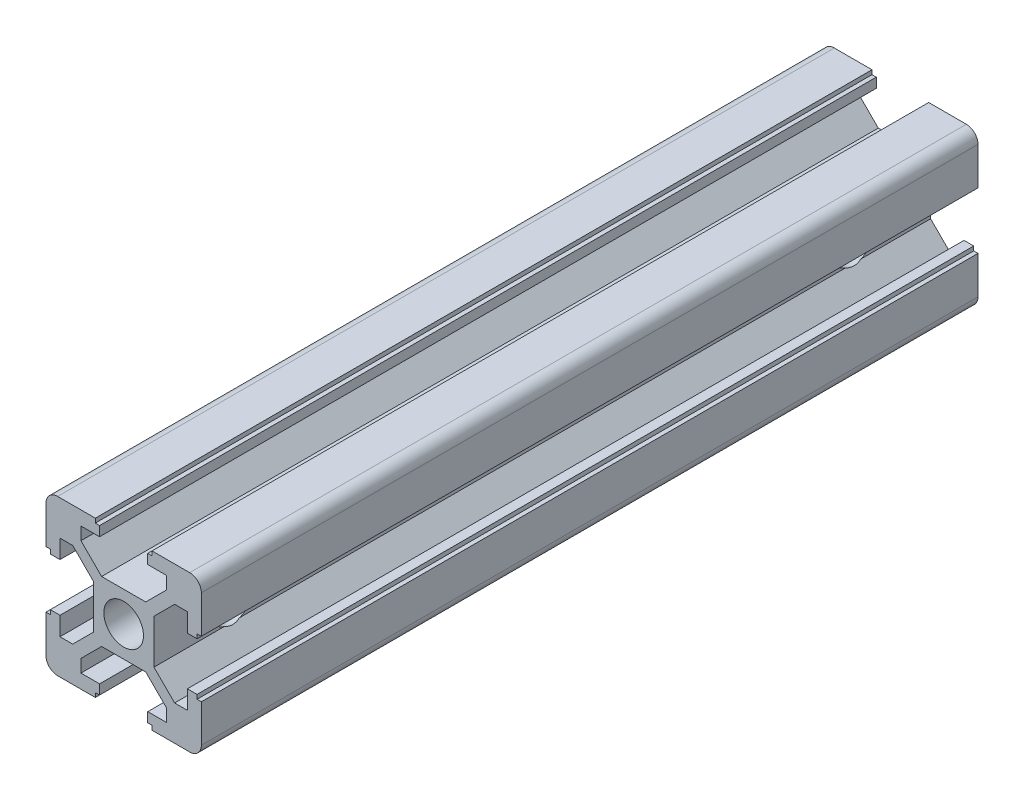
SolidWorks part; units mm, degrees
material "6063-T5"
ref_plane "前视基准面" through (0, 0, 0) normal (0, 0, 1) x (1, 0, 0)
ref_plane "上视基准面" through (0, 0, 0) normal (0, 1, 0) x (1, 0, 0)
ref_plane "右视基准面" through (0, 0, 0) normal (1, 0, 0) x (0, 0, -1)
sketch "草图2" plane through (0, 0, 0) normal (0, 0, 1) x (1, 0, 0)
  line L0 (-3.9, 2.8393) -> (-6.5607, 5.5)
  line L1 (-2.8393, 3.9) -> (2.8393, 3.9)
  line L2 (-3.9, 2.8393) -> (-3.9, -2.8393)
  line L3 (-2.8393, -3.9) -> (2.8393, -3.9)
  line L4 (3.9, 2.8393) -> (3.9, -2.8393)
  line L5 (-3.9, 3.9) -> (3.9, -3.9) construction
  line L6 (-3.9, -3.9) -> (3.9, 3.9) construction
  line L7 (-2.8393, 3.9) -> (-5.5, 6.5607)
  line L8 (-5.5, 6.5607) -> (-5.5, 8.2)
  line L9 (-5.5, 8.2) -> (-3.1, 8.2)
  line L10 (-3.1, 8.2) -> (-3.1, 9.45)
  line L11 (-3.1, 9.45) -> (-3.65, 9.45)
  line L12 (-3.65, 9.45) -> (-3.65, 10)
  line L13 (-3.65, 10) -> (-8.5, 10)
  line L14 (-6.5607, 5.5) -> (-8.2, 5.5)
  line L15 (-10, 3.65) -> (-10, 8.5)
  line L16 (-9.45, 3.65) -> (-10, 3.65)
  line L17 (-9.45, 3.1) -> (-9.45, 3.65)
  line L18 (-8.2, 3.1) -> (-9.45, 3.1)
  line L19 (-8.2, 5.5) -> (-8.2, 3.1)
  line L20 (2.8393, 3.9) -> (5.5, 6.5607)
  line L21 (3.9, 2.8393) -> (6.5607, 5.5)
  line L22 (6.5607, 5.5) -> (8.2, 5.5)
  line L23 (8.2, 5.5) -> (8.2, 3.1)
  line L24 (8.2, 3.1) -> (9.45, 3.1)
  line L25 (9.45, 3.1) -> (9.45, 3.65)
  line L26 (9.45, 3.65) -> (10, 3.65)
  line L27 (10, 3.65) -> (10, 8.5)
  line L28 (5.5, 6.5607) -> (5.5, 8.2)
  line L29 (3.65, 10) -> (8.5, 10)
  line L30 (3.65, 9.45) -> (3.65, 10)
  line L31 (3.1, 9.45) -> (3.65, 9.45)
  line L32 (3.1, 8.2) -> (3.1, 9.45)
  line L33 (5.5, 8.2) -> (3.1, 8.2)
  line L34 (3.9, -2.8393) -> (6.5607, -5.5)
  line L35 (2.8393, -3.9) -> (5.5, -6.5607)
  line L36 (5.5, -6.5607) -> (5.5, -8.2)
  line L37 (5.5, -8.2) -> (3.1, -8.2)
  line L38 (3.1, -8.2) -> (3.1, -9.45)
  line L39 (3.1, -9.45) -> (3.65, -9.45)
  line L40 (3.65, -9.45) -> (3.65, -10)
  line L41 (3.65, -10) -> (8.5, -10)
  line L42 (6.5607, -5.5) -> (8.2, -5.5)
  line L43 (10, -3.65) -> (10, -8.5)
  line L44 (9.45, -3.65) -> (10, -3.65)
  line L45 (9.45, -3.1) -> (9.45, -3.65)
  line L46 (8.2, -3.1) -> (9.45, -3.1)
  line L47 (8.2, -5.5) -> (8.2, -3.1)
  line L48 (-2.8393, -3.9) -> (-5.5, -6.5607)
  line L49 (-3.9, -2.8393) -> (-6.5607, -5.5)
  line L50 (-6.5607, -5.5) -> (-8.2, -5.5)
  line L51 (-8.2, -5.5) -> (-8.2, -3.1)
  line L52 (-8.2, -3.1) -> (-9.45, -3.1)
  line L53 (-9.45, -3.1) -> (-9.45, -3.65)
  line L54 (-9.45, -3.65) -> (-10, -3.65)
  line L55 (-10, -3.65) -> (-10, -8.5)
  line L56 (-5.5, -6.5607) -> (-5.5, -8.2)
  line L57 (-3.65, -10) -> (-8.5, -10)
  line L58 (-3.65, -9.45) -> (-3.65, -10)
  line L59 (-3.1, -9.45) -> (-3.65, -9.45)
  line L60 (-3.1, -8.2) -> (-3.1, -9.45)
  line L61 (-5.5, -8.2) -> (-3.1, -8.2)
  circle A0 centre (0, 0) radius 2.55
  arc A1 (-8.5, 10) -> (-10, 8.5) centre (-8.5, 8.5) ccw
  arc A2 (10, 8.5) -> (8.5, 10) centre (8.5, 8.5) ccw
  arc A3 (8.5, -10) -> (10, -8.5) centre (8.5, -8.5) ccw
  arc A4 (-10, -8.5) -> (-8.5, -10) centre (-8.5, -8.5) ccw
  point P25 (-10, 10)
  point P79 (0, 0)
  dimension "D1" = 5.1
  dimension "D9" = 1.5
  dimension "D2" = 7.8
  dimension "D3" = 1.5
  dimension "D4" = 10
  dimension "D5" = 3.1
  dimension "D6" = 0.55
  dimension "D7" = 1.8
  dimension "D8" = 5.5
  dimension "D11" = 3.9
  dimension "D10" = 4
extrude "凸台-拉伸1" add sketch "草图2" along normal blind 100
sketch "草图3" plane through (10, 0, 0) normal (1, 0, 0) x (0, 0, -1)
  line L0 (-100, 0) -> (0, 0) construction
  line L1 (-100, -2.8393) -> (-100, 2.8393) construction
  circle A2 centre (-90, 0) radius 3
  circle A3 centre (-10, 0) radius 3
  dimension "D1" = 6
  dimension "D2" = 6
  dimension "D3" = 80
  dimension "D4" = 10
extrude "切除-拉伸1" cut sketch "草图3" against normal through all
